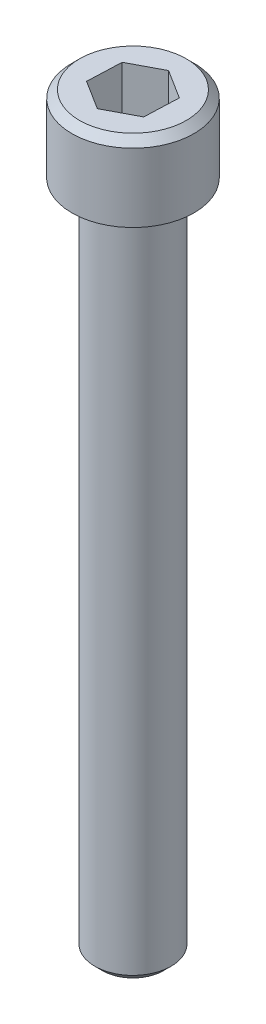
SolidWorks part; units mm, degrees
ref_plane "Front Plane" through (0, 0, 0) normal (0, 0, 1) x (1, 0, 0)
ref_plane "Top Plane" through (0, 0, 0) normal (0, 1, 0) x (1, 0, 0)
ref_plane "Right Plane" through (0, 0, 0) normal (1, 0, 0) x (0, 0, -1)
sketch "Sketch1" plane through (0, 0, 0) normal (0, 1, 0) x (1, 0, 0)
  circle A0 centre (0, 0) radius 5
  dimension "D1" = 10
extrude "Boss-Extrude1" add sketch "Sketch1" along normal blind 88
cosmetic thread "Cosmetic Thread1" parameters "D1"=23, "D2"=9
sketch "Sketch2" plane through (0, 88, 0) normal (0, 1, 0) x (1, 0, 0)
  circle A0 centre (0, 0) radius 8
  dimension "D1" = 16
extrude "Boss-Extrude2" add sketch "Sketch2" along normal blind 10
sketch "Sketch3" plane through (0, 0, 0) normal (0, 0, 1) x (1, 0, 0)
  line L0 (8, 98) -> (8, 97)
  line L1 (8, 98) -> (-8, 98) construction
  line L3 (0, 98) -> (0, 88.121) construction
  line L4 (8, 97) -> (7, 98)
  line L5 (7, 98) -> (8, 98)
  dimension "D1" = 1
  dimension "D2" = 1
  dimension "D3" = 7
revolve "Cut-Revolve1" cut sketch "Sketch3" angle 360 about L3
sketch "Sketch4" plane through (0, 0, 0) normal (0, 0, 1) x (1, 0, 0)
  line L0 (0, 0) -> (0, 5.4841) construction
  line L1 (5, 0) -> (4, 0)
  line L2 (-5, 0) -> (5, 0) construction
  line L3 (4, 0) -> (5, 1)
  line L4 (5, 0) -> (5, 88) construction
  line L5 (5, 1) -> (5, 0)
  dimension "D1" = 1
  dimension "D2" = 1
revolve "Cut-Revolve2" cut sketch "Sketch4" angle 360 about L0
sketch "Sketch5" plane through (0, 98, 0) normal (0, 1, 0) x (1, 0, 0)
  line L1 (3.9804, 2.0991) -> (0.1724, 4.4967)
  line L2 (0.1724, 4.4967) -> (-3.8081, 2.3976)
  line L3 (-3.8081, 2.3976) -> (-3.9804, -2.0991)
  line L4 (-3.9804, -2.0991) -> (-0.1724, -4.4967)
  line L5 (-0.1724, -4.4967) -> (3.8081, -2.3976)
  line L6 (3.8081, -2.3976) -> (3.9804, 2.0991)
  circle A0 centre (0, 0) radius 4.5
  circle A1 centre (0, 0) radius 3.8971 construction
  dimension "D1" = 9
  dimension "D2" = 3.9804
  dimension "D3" = 3.8971
extrude "Cut-Extrude1" cut sketch "Sketch5" against normal blind 7 contours L5 L6 L1 L2 L3 L4
